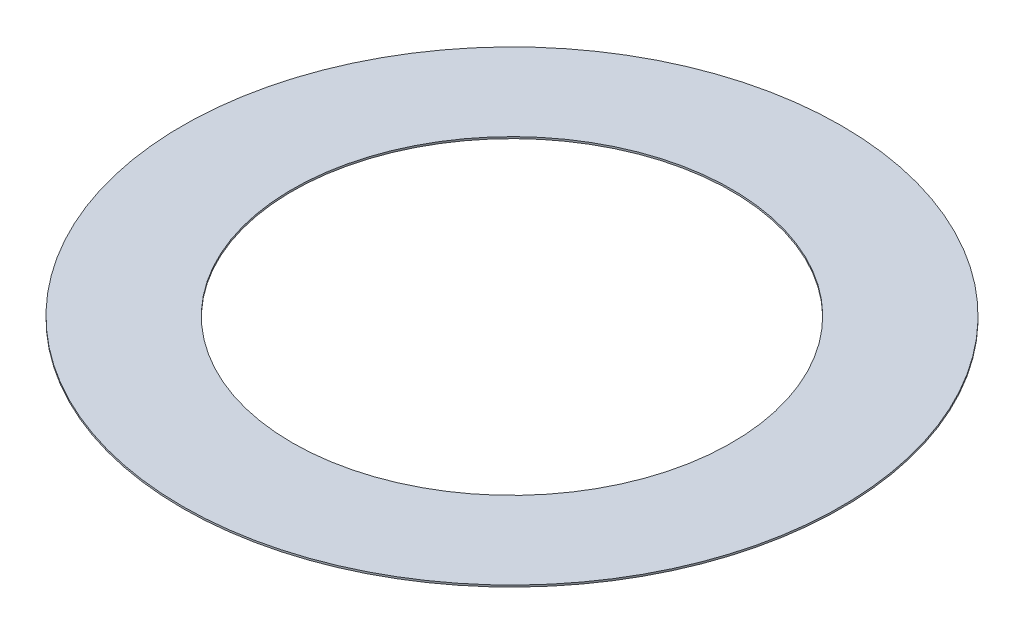
SolidWorks part; units mm, degrees
ref_plane "Front Plane" through (0, 0, 0) normal (0, 0, 1) x (1, 0, 0)
ref_plane "Top Plane" through (0, 0, 0) normal (0, 1, 0) x (1, 0, 0)
ref_plane "Right Plane" through (0, 0, 0) normal (1, 0, 0) x (0, 0, -1)
sketch "Sketch1" plane through (0, 0, 0) normal (0, 1, 0) x (1, 0, 0)
  circle A0 centre (0, 0) radius 3.175
  circle A1 centre (0, 0) radius 4.7625
  dimension "D1" = 6.35
  dimension "D2" = 9.525
extrude "Boss-Extrude1" add sketch "Sketch1" along normal blind 0.0254
